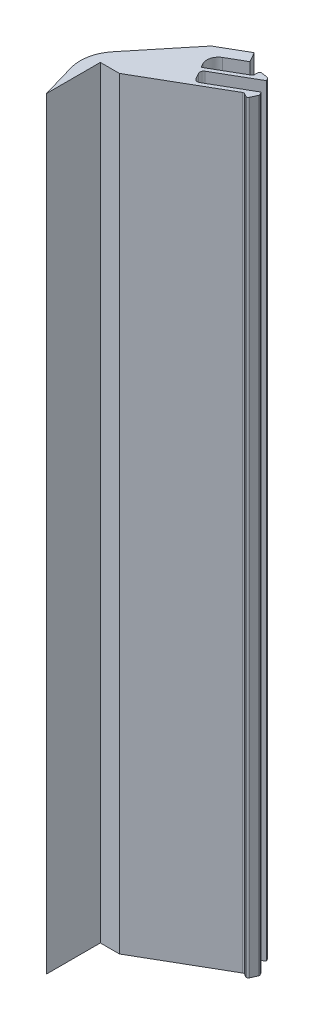
SolidWorks part; units mm, degrees
ref_plane "Front Plane" through (0, 0, 0) normal (0, 0, 1) x (1, 0, 0)
ref_plane "Top Plane" through (0, 0, 0) normal (0, 1, 0) x (1, 0, 0)
ref_plane "Right Plane" through (0, 0, 0) normal (1, 0, 0) x (0, 0, -1)
sketch "Sketch1" plane through (0, 0, 0) normal (0, 1, 0) x (1, 0, 0)
  line L0 (13.9271, 14.1754) -> (16.352, 13.8433)
  line L1 (16.352, 13.8433) -> (16.852, 12.9773)
  line L2 (13.9271, 14.1754) -> (13.9271, 12.4433)
  line L3 (2.5947, 5.9005) -> (3.0596, 5.0142)
  line L4 (13.9271, 12.4433) -> (2.5947, 5.9005)
  line L5 (18.752, 9.6864) -> (19.252, 8.8204)
  line L6 (19.252, 8.8204) -> (18.1539, 6.4543)
  line L7 (18.1539, 6.4543) -> (16.6539, 7.3204)
  line L8 (16.6539, 7.3204) -> (5.1142, 0.6579)
  line L9 (16.852, 12.9773) -> (3.0596, 5.0142)
  line L10 (18.752, 9.6864) -> (4.7191, 1.5845)
  line L11 (4.7191, 1.5845) -> (5.1142, 0.6579)
  dimension "D1" = 1
  dimension "D2" = 1
  dimension "D3" = 2.5
  dimension "D4" = 1
  dimension "D5" = 1
  dimension "D6" = 60
  dimension "D7" = 60
  dimension "D8" = 3
  dimension "D9" = 2.5
  dimension "D10" = 3.8
extrude "Boss-Extrude1" add sketch "Sketch1" along normal blind 200
fillet "Fillet1" radius 0.5 3 edges at (19.252, 100, -8.8204) (18.1539, 100, -6.4543) (16.6539, 100, -7.3204)
fillet "Fillet2" radius 0.5 3 edges at (16.352, 100, -13.8433) (13.9271, 100, -14.1754) (13.9271, 100, -12.4433)
sketch "Sketch2" plane through (0, 0, 0) normal (0, 1, 0) x (1, 0, 0)
  line L0 (8.1826, 2.4295) -> (3.2326, 11.0031)
  line L1 (5.1142, 0.6579) -> (16.4039, 7.176) construction
  line L2 (1.7326, 13.6012) -> (-13.1637, -4.6475)
  line L3 (-13.1637, -4.6475) -> (-9.0751, -18.7873)
  line L4 (-9.0751, -5.3031) -> (-9.0751, -305.3031) construction
  line L5 (-9.0751, -18.7873) -> (-9.0751, -4.6475)
  line L6 (-9.0751, -4.6475) -> (-4.0751, -4.6475)
  line L7 (8.1826, 2.4295) -> (-4.0751, -4.6475)
  line L8 (9.6431, 16.4363) -> (12.0181, 12.3227) construction
  line L9 (14.3058, 20.8603) -> (10.1922, 18.4853) construction
  line L10 (-4.0751, -5.3031) -> (-9.0751, -5.3031) construction
  line L11 (-4.0751, 60.1969) -> (-4.0751, -370.8031) construction
  line L12 (3.2326, 11.0031) -> (10.3931, 15.1372)
  line L13 (10.3931, 15.1372) -> (8.8931, 17.7353)
  line L14 (8.8931, 17.7353) -> (1.7326, 13.6012)
  dimension "D1" = 3
extrude "Boss-Extrude3" add sketch "Sketch2" along normal up to surface (200 mm away) up to face at (12.3433, 200, -11.5854)
fillet "Fillet3" radius 10 1 edges at (-13.1637, 100, 4.6475)
fillet "Fillet4" radius 1 2 edges at (5.7826, 100, -6.5864) (7.6826, 100, -3.2955)
fillet "Fillet5" radius 3 1 edges at (3.2326, 100, -11.0031)
